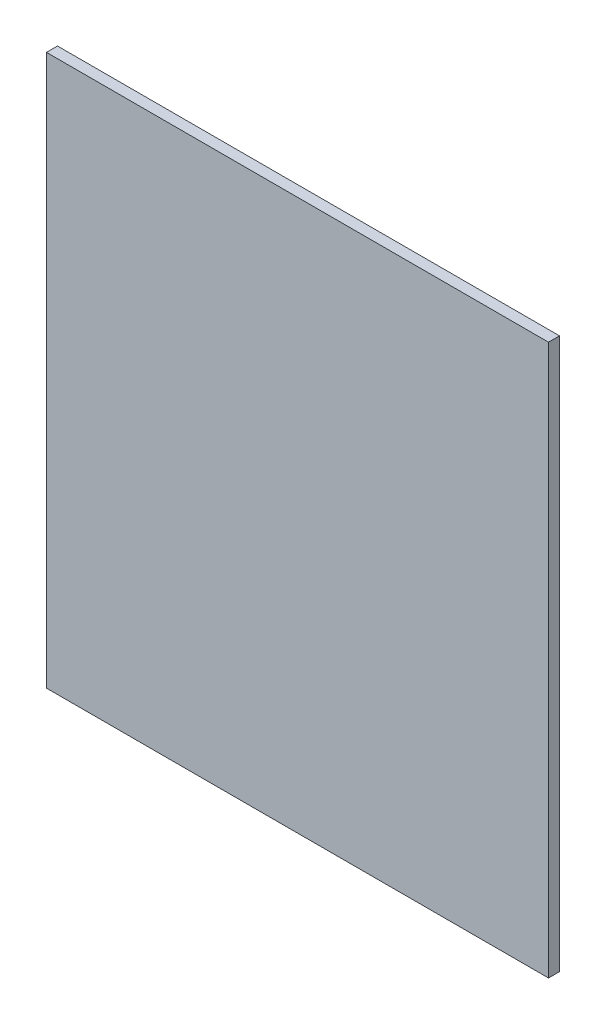
SolidWorks part; units mm, degrees
ref_plane "Front Plane" through (0, 0, 0) normal (0, 0, 1) x (1, 0, 0)
ref_plane "Top Plane" through (0, 0, 0) normal (0, 1, 0) x (1, 0, 0)
ref_plane "Right Plane" through (0, 0, 0) normal (1, 0, 0) x (0, 0, -1)
sketch "Sketch1" plane through (0, 0, 0) normal (0, 0, 1) x (1, 0, 0)
  line L0 (-68.375, -75) -> (68.375, 75) construction
  line L1 (-68.375, 75) -> (68.375, 75)
  line L2 (-68.375, 75) -> (-68.375, -75)
  line L3 (-68.375, -75) -> (68.375, -75)
  line L4 (68.375, 75) -> (68.375, -75)
  line L5 (68.375, -75) -> (-68.375, 75) construction
  dimension "D1" = 136.75
  dimension "D2" = 150
extrude "Boss-Extrude1" add sketch "Sketch1" along normal blind 3
